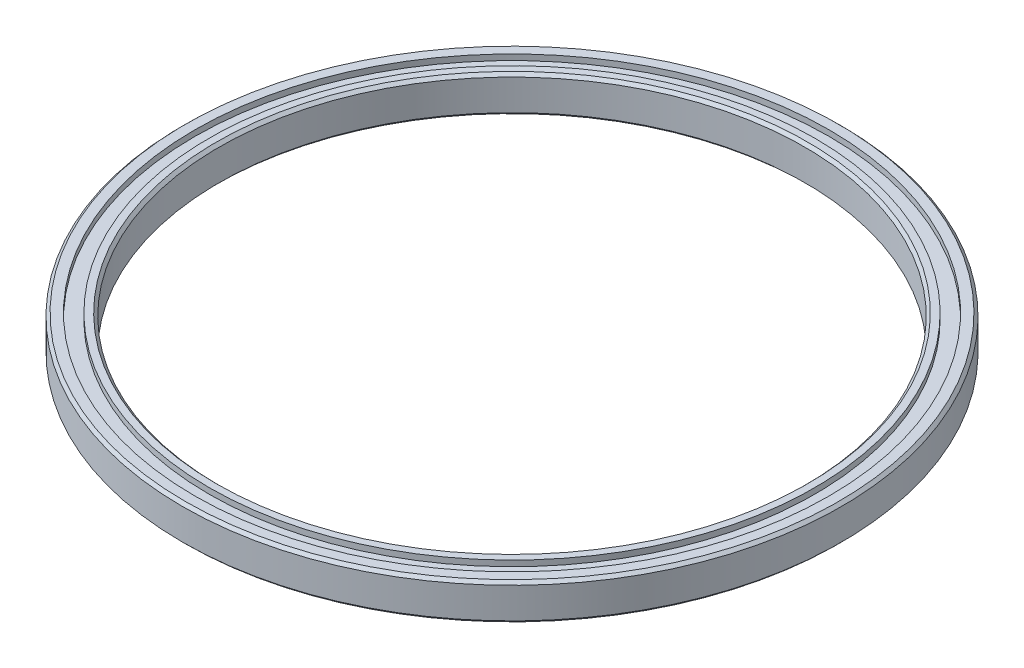
SolidWorks part; units mm, degrees
material "AISI 304"
ref_plane "前视基准面" through (0, 0, 0) normal (0, 0, 1) x (1, 0, 0)
ref_plane "上视基准面" through (0, 0, 0) normal (0, 1, 0) x (1, 0, 0)
ref_plane "右视基准面" through (0, 0, 0) normal (1, 0, 0) x (0, 0, -1)
sketch "草图1" plane through (0, 0, 0) normal (0, 1, 0) x (1, 0, 0)
  circle A0 centre (0, 0) radius 50.8
  circle A1 centre (0, 0) radius 57.15
  dimension "D1" = 114.3
  dimension "D2" = 101.6
extrude "凸台-拉伸1" add sketch "草图1" along normal blind 6.35
sketch "草图2" plane through (0, 6.35, 0) normal (0, 1, 0) x (1, 0, 0)
  circle A0 centre (0, 0) radius 52.5
  circle A1 centre (0, 0) radius 55
  dimension "D1" = 105
  dimension "D2" = 110
extrude "切除-拉伸1" cut sketch "草图2" against normal blind 1
sketch "草图3" plane through (0, 0, 0) normal (0, -1, 0) x (1, 0, 0)
  circle A0 centre (0, 0) radius 52.5
  circle A1 centre (0, 0) radius 55
  dimension "D1" = 105
  dimension "D2" = 110
extrude "切除-拉伸2" cut sketch "草图3" against normal blind 1
chamfer "倒角1" distance 0.5 angle 45 4 edges at (0, 6.35, 50.8) (0, 6.35, 57.15) (0, 0, 50.8) (0, 0, 57.15)
